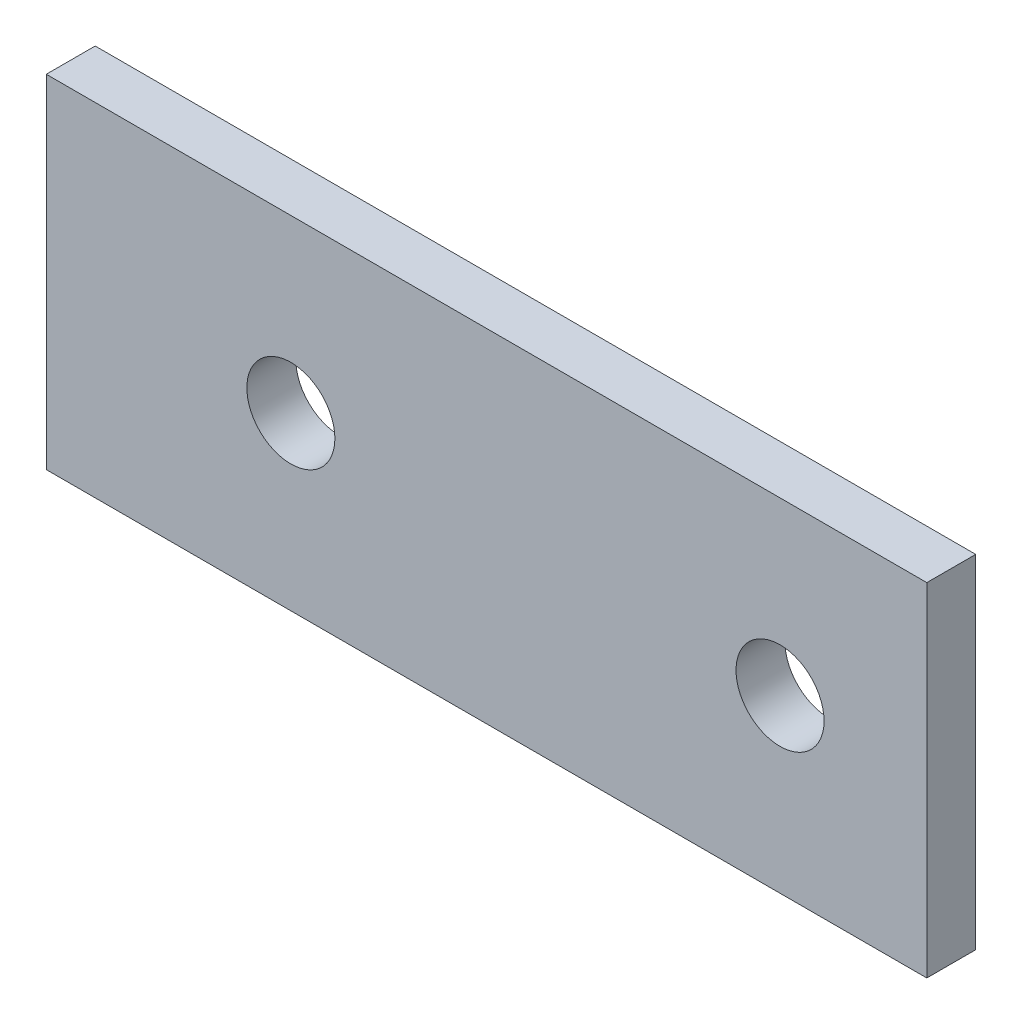
SolidWorks part; units mm, degrees
material "Plain Carbon Steel"
ref_plane "Front Plane" through (0, 0, 0) normal (0, 0, 1) x (1, 0, 0)
ref_plane "Top Plane" through (0, 0, 0) normal (0, 1, 0) x (1, 0, 0)
ref_plane "Right Plane" through (0, 0, 0) normal (1, 0, 0) x (0, 0, -1)
sketch "Sketch1" plane through (0, 0, 0) normal (0, 0, 1) x (1, 0, 0)
  line L1 (-90, 35) -> (90, 35)
  line L2 (-90, 35) -> (-90, -35)
  line L3 (-90, -35) -> (90, -35)
  line L4 (90, 35) -> (90, -35)
  line L5 (-90, 35) -> (90, -35) construction
  line L6 (-90, -35) -> (90, 35) construction
  circle A0 centre (60, 0) radius 9
  circle A1 centre (-40, 0) radius 9
  point P0 (0, 0)
  point P10 (90, 0)
  dimension "D3" = 18
  dimension "D4" = 18
  dimension "D5" = 30
  dimension "D6" = 100
  dimension "D1" = 70
  dimension "D2" = 180
extrude "Boss-Extrude1" add sketch "Sketch1" along normal mid plane 10
